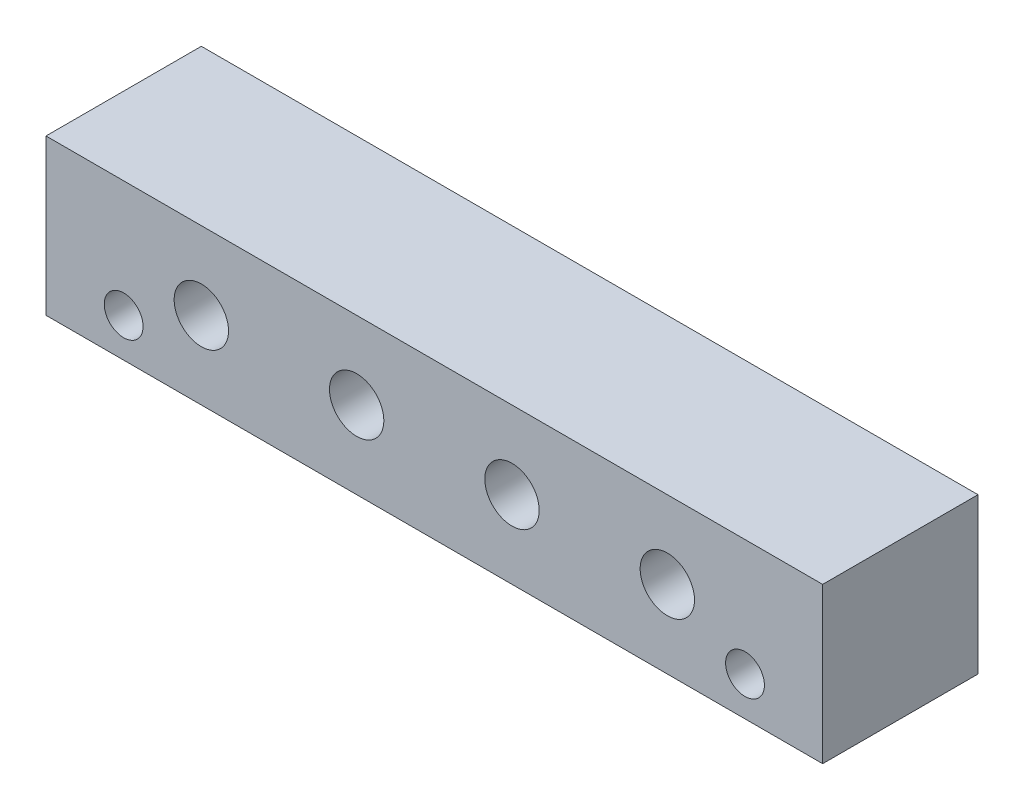
SolidWorks part; units mm, degrees
ref_plane "Plan de face" through (0, 0, 0) normal (0, 0, 1) x (1, 0, 0)
ref_plane "Plan de dessus" through (0, 0, 0) normal (0, 1, 0) x (1, 0, 0)
ref_plane "Plan de droite" through (0, 0, 0) normal (1, 0, 0) x (0, 0, -1)
sketch "Esquisse1" plane through (0, 0, 0) normal (0, 0, 1) x (1, 0, 0)
  line L0 (0, 5) -> (50, 5) construction
  line L1 (0, 0) -> (50, 0)
  line L2 (0, 0) -> (0, 10)
  line L3 (0, 10) -> (50, 10)
  line L4 (50, 0) -> (50, 10)
  line L5 (50, 2.5) -> (0, 2.5) construction
  circle A0 centre (5, 2.5) radius 1.25
  circle A1 centre (45, 2.5) radius 1.25
  circle A2 centre (40, 5) radius 1.75
  circle A3 centre (30, 5) radius 1.75
  circle A4 centre (20, 5) radius 1.75
  circle A5 centre (10, 5) radius 1.75
  point P10 (0, 5)
  point P14 (25, 5)
  dimension "D6" = 2.5
  dimension "D8" = 3.5
  dimension "D1" = 10
  dimension "D2" = 50
  dimension "D3" = 2.5
  dimension "D4" = 40
  dimension "D5" = 5
  dimension "D7" = 15
  dimension "D9" = 4
extrude "Boss.-Extru.1" add sketch "Esquisse1" along normal blind 10
